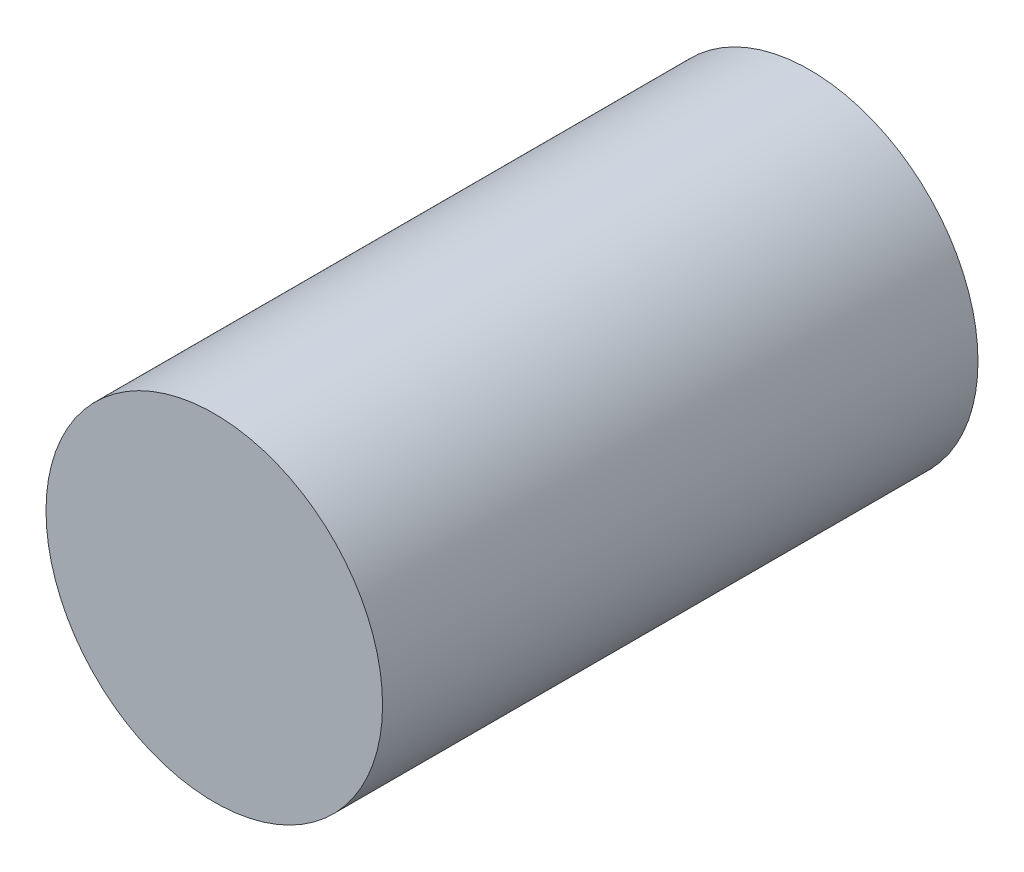
SolidWorks part; units mm, degrees
ref_plane "Front Plane" through (0, 0, 0) normal (0, 0, 1) x (1, 0, 0)
ref_plane "Top Plane" through (0, 0, 0) normal (0, 1, 0) x (1, 0, 0)
ref_plane "Right Plane" through (0, 0, 0) normal (1, 0, 0) x (0, 0, -1)
sketch "Sketch2" plane through (0, 0, 0) normal (0, 0, 1) x (1, 0, 0)
  circle A0 centre (0, 0) radius 3.9
  dimension "D1" = 7.8
extrude "Boss-Extrude1" add sketch "Sketch2" along normal blind 13.8
